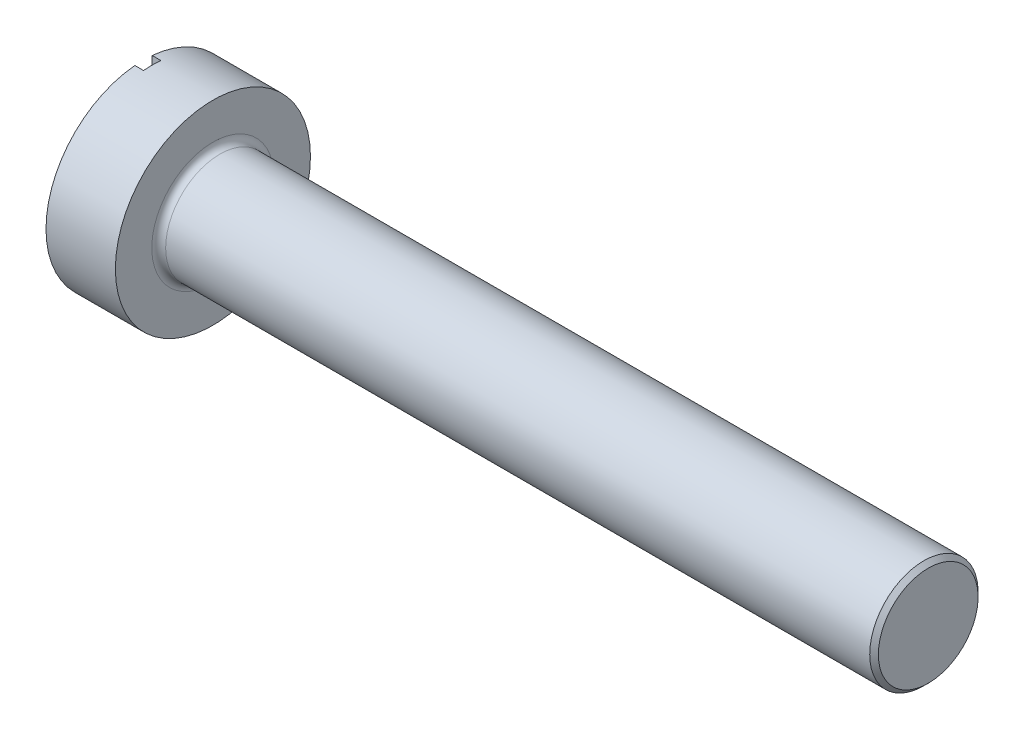
SolidWorks part; units mm, degrees
ref_plane "Front Plane" through (0, 0, 0) normal (0, 0, 1) x (1, 0, 0)
ref_plane "Top Plane" through (0, 0, 0) normal (0, 1, 0) x (1, 0, 0)
ref_plane "Right Plane" through (0, 0, 0) normal (1, 0, 0) x (0, 0, -1)
sketch "Sketch1" plane through (0, 0, 0) normal (0, 0, 1) x (1, 0, 0)
  line L0 (0, 0) -> (0, 2.25)
  line L1 (0, 2.25) -> (1.6, 2.25)
  line L2 (1.6, 2.25) -> (1.6, 0.75)
  line L3 (0, 0) -> (18.1, 0)
  line L4 (18.1, 0) -> (18.1, 1.25)
  line L5 (18.1, 1.25) -> (1.6, 1.25)
  dimension "D1" = 2.25
  dimension "D2" = 1.6
  dimension "D3" = 16.5
  dimension "D4" = 1.25
revolve "Revolve1" add sketch "Sketch1" angle 360 about L3
chamfer "Chamfer1" distance 0.1 angle 45 1 edges at (18.1, 0, 1.25)
fillet "Fillet1" radius 0.16 1 edges at (1.6, 0, 1.25)
sketch "Sketch2" plane through (0, 0, 0) normal (0, 1, 0) x (1, 0, 0)
  line L1 (0, 0) -> (0.2, 0)
  line L2 (0, 0) -> (0, 0.2)
  line L3 (0, 0.2) -> (0.2, 0.2)
  line L4 (0.2, 0) -> (0.2, 0.2)
  line L5 (0, 0) -> (0.2, 0)
  line L6 (0, 0) -> (0, -0.2)
  line L7 (0, -0.2) -> (0.2, -0.2)
  line L8 (0.2, 0) -> (0.2, -0.2)
extrude "Extrude1" cut sketch "Sketch2" against normal through all both and the other way through all contours L8 L1 L6 L7 | L1 L4 L3 L2
